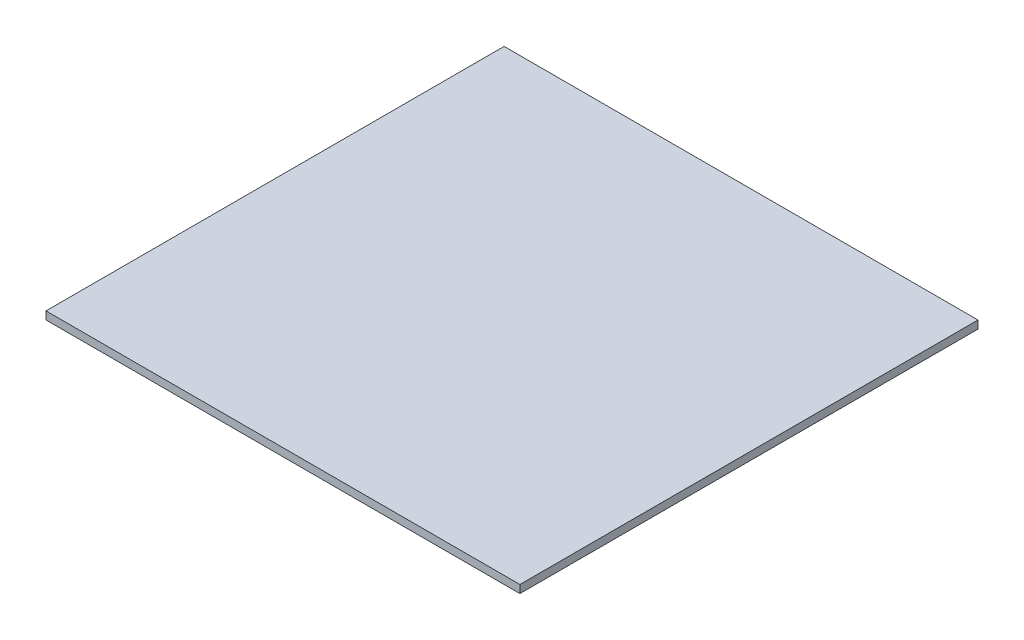
SolidWorks part; units mm, degrees
material "Teak"
ref_plane "Front Plane" through (0, 0, 0) normal (0, 0, 1) x (1, 0, 0)
ref_plane "Top Plane" through (0, 0, 0) normal (0, 1, 0) x (1, 0, 0)
ref_plane "Right Plane" through (0, 0, 0) normal (1, 0, 0) x (0, 0, -1)
sketch "Sketch1" plane through (0, 0, 0) normal (0, 1, 0) x (1, 0, 0)
  line L1 (0, 0) -> (762, 0)
  line L2 (0, 0) -> (0, 736.6)
  line L3 (0, 736.6) -> (762, 736.6)
  line L4 (762, 0) -> (762, 736.6)
  dimension "D1" = 762
  dimension "D2" = 736.6
extrude "Boss-Extrude1" add sketch "Sketch1" along normal blind 12.7
